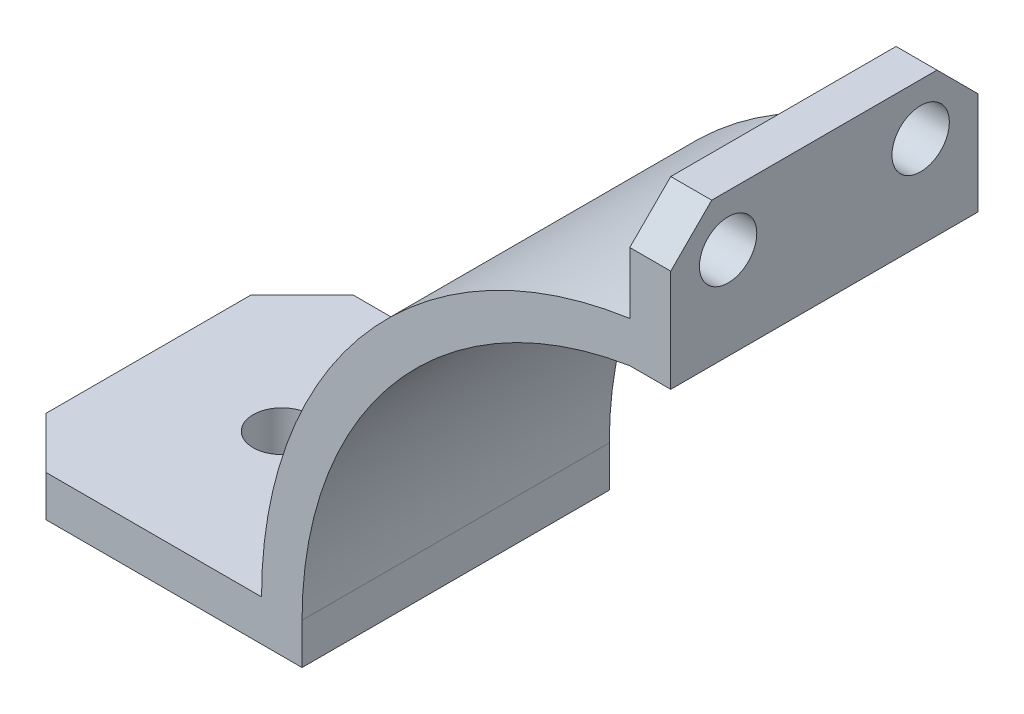
SolidWorks part; units mm, degrees
ref_plane "Front Plane" through (0, 0, 0) normal (0, 0, 1) x (1, 0, 0)
ref_plane "Top Plane" through (0, 0, 0) normal (0, 1, 0) x (1, 0, 0)
ref_plane "Right Plane" through (0, 0, 0) normal (1, 0, 0) x (0, 0, -1)
sketch "Sketch1" plane through (0, 0, 0) normal (0, 0, 1) x (1, 0, 0)
  line L0 (0, 0) -> (0, 50000) construction
  line L2 (-19, 0) -> (-19, -2)
  line L3 (-19, -2) -> (-34, -2)
  line L4 (-34, -2) -> (-34, 0)
  line L5 (-34, 0) -> (-20.9773, 0)
  line L6 (-3, 20.7617) -> (-3, 25.7617)
  line L7 (-3, 25.7617) -> (-1, 25.7617)
  line L8 (-1, 25.7617) -> (-1, 18.7617)
  line L9 (-1, 18.7617) -> (-3, 18.7617)
  arc A0 (-19, 0) -> (-3, 18.7617) centre (0, 0) cw
  arc A1 (-20.9773, 0) -> (-3, 20.7617) centre (0, 0) cw
  dimension "D2" = 19
  dimension "D1" = 2
  dimension "D3" = 15
  dimension "D4" = 2
  dimension "D5" = 2
  dimension "D6" = 7
  dimension "D7" = 1
extrude "Boss-Extrude1" add sketch "Sketch1" along normal blind 15
chamfer "Chamfer1" distance 2.5 2 edges at (-34, -1, 0) (-34, -1, 15)
sketch "Sketch2" plane through (-3, 0, 0) normal (-1, 0, 0) x (0, 0, 1)
  line L0 (15, 25.7617) -> (15, 20.7617) construction
  line L1 (0, 25.7617) -> (0, 20.7617) construction
  circle A0 centre (2.8, 23.2617) radius 1.4
  circle A1 centre (12.2, 23.2617) radius 1.4
  point P8 (0, 23.2617)
  dimension "D1" = 2.8
  dimension "D2" = 2.8
  dimension "D3" = 2.8
extrude "Cut-Extrude1" cut sketch "Sketch2" against normal blind 15
chamfer "Chamfer2" distance 2 angle 45 2 edges at (-2, 25.7617, 15) (-2, 25.7617, 0)
sketch "Sketch3" plane through (0, 0, 0) normal (0, 1, 0) x (1, 0, 0)
  line L0 (-34, -12.5) -> (-34, -2.5) construction
  line L2 (-20.9773, 0) -> (-34, 0.1) construction
  line L3 (45.4373, 0.1) -> (-44.4791, 0.1) construction
  circle A0 centre (-27.4886, -7.5) radius 1.4
  point P2 (-27.4886, 0.05)
  point P5 (-34, -7.5)
  point P6 (-27.2849, -7.5)
  dimension "D1" = 2.8
extrude "Cut-Extrude2" cut sketch "Sketch3" against normal through all contours A0
